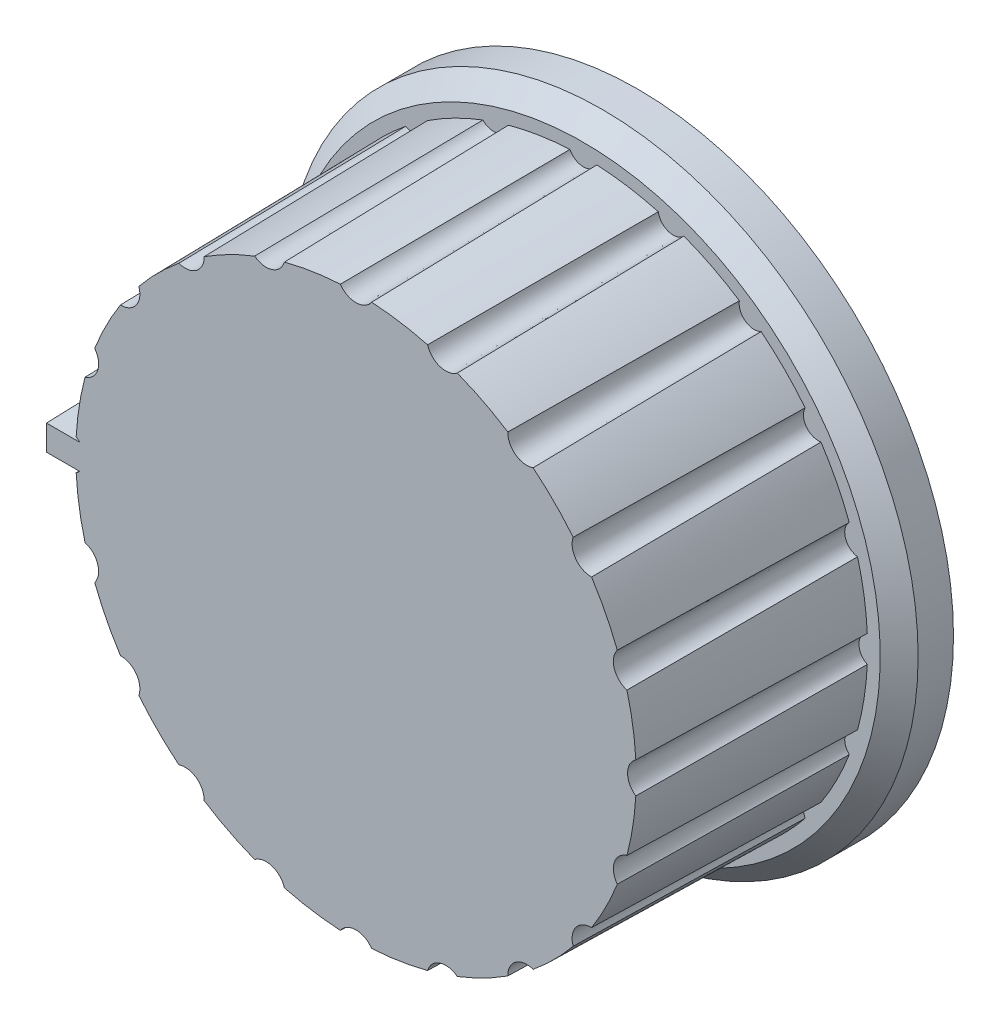
SolidWorks part; units mm, degrees
ref_plane "Front Plane" through (0, 0, 0) normal (0, 0, 1) x (1, 0, 0)
ref_plane "Top Plane" through (0, 0, 0) normal (0, 1, 0) x (1, 0, 0)
ref_plane "Right Plane" through (0, 0, 0) normal (1, 0, 0) x (0, 0, -1)
sketch "Sketch1" plane through (0, 0, 0) normal (0, 0, 1) x (1, 0, 0)
  circle A0 centre (0, 0) radius 25
  dimension "D1" = 50
extrude "Boss-Extrude1" add sketch "Sketch1" along normal blind 4.3
sketch "Sketch2" plane through (0, 0, 4.3) normal (0, 0, 1) x (1, 0, 0)
  circle A0 centre (0, 0) radius 22.5
  dimension "D1" = 45
extrude "Boss-Extrude2" add sketch "Sketch2" along normal blind 18 draft 1
chamfer "Chamfer1" distance 1.5 angle 45 1 edges at (25, 0, 4.3)
sketch "Sketch3" plane through (0, 0, 22.3) normal (0, 0, 1) x (1, 0, 0)
  circle A0 centre (0, 23) radius 1.5
  circle A1 centre (7.1074, 21.8743) radius 1.5
  circle A2 centre (13.5191, 18.6074) radius 1.5
  circle A3 centre (18.6074, 13.5191) radius 1.5
  circle A4 centre (21.8743, 7.1074) radius 1.5
  circle A5 centre (23, 0) radius 1.5
  circle A6 centre (21.8743, -7.1074) radius 1.5
  circle A7 centre (18.6074, -13.5191) radius 1.5
  circle A8 centre (13.5191, -18.6074) radius 1.5
  circle A9 centre (7.1074, -21.8743) radius 1.5
  circle A10 centre (0, -23) radius 1.5
  circle A11 centre (-7.1074, -21.8743) radius 1.5
  circle A12 centre (-13.5191, -18.6074) radius 1.5
  circle A13 centre (-18.6074, -13.5191) radius 1.5
  circle A14 centre (-21.8743, -7.1074) radius 1.5
  circle A15 centre (-23, 0) radius 1.5
  circle A16 centre (-21.8743, 7.1074) radius 1.5
  circle A17 centre (-18.6074, 13.5191) radius 1.5
  circle A18 centre (-13.5191, 18.6074) radius 1.5
  circle A19 centre (-7.1074, 21.8743) radius 1.5
  point P2 (6.6598, 0.5658)
  point P4 (0, 0)
  point P44 (0, 0)
  dimension "D1" = 3
  dimension "D2" = 23
  dimension "D3" = 20
extrude "Cut-Extrude2" cut sketch "Sketch3" against normal blind 18 draft 1
sketch "Sketch4" plane through (0, 0, 22.3) normal (0, 0, 1) x (1, 0, 0)
  line L1 (-24.5, 1) -> (-17.5, 1)
  line L2 (-24.5, 1) -> (-24.5, -1)
  line L3 (-24.5, -1) -> (-17.5, -1)
  line L4 (-17.5, 1) -> (-17.5, -1)
  dimension "D1" = 17.5
  dimension "D2" = 2
  dimension "D3" = 1
  dimension "D4" = 7
extrude "Boss-Extrude3" add sketch "Sketch4" against normal blind 21 draft 1 draft outward yes
sketch "Sketch5" plane through (0, 0, 0) normal (0, 0, -1) x (-1, 0, 0)
  circle A0 centre (0, 0) radius 5.9
  dimension "D1" = 11.8
extrude "Cut-Extrude3" cut sketch "Sketch5" against normal blind 3
sketch "Sketch7" plane through (0, 0, 3) normal (0, 0, -1) x (-1, 0, 0)
  circle A0 centre (0, 0) radius 3
  dimension "D1" = 6
extrude "Cut-Extrude4" cut sketch "Sketch7" against normal blind 11
sketch "Sketch8" plane through (0, 0, 3) normal (0, 0, -1) x (-1, 0, 0)
  line L1 (-2.9732, 0.4) -> (2.9732, 0.4)
  line L2 (-2.9732, 0.4) -> (-2.9732, -0.4)
  line L3 (-2.9732, -0.4) -> (2.9732, -0.4)
  line L4 (2.9732, 0.4) -> (2.9732, -0.4)
  circle A0 centre (0, 0) radius 3 construction
  circle A1 centre (0, 0) radius 3 construction
  dimension "D1" = 0.8
  dimension "D2" = 0.4
extrude "Boss-Extrude4" add sketch "Sketch8" against normal blind 12 separate body
